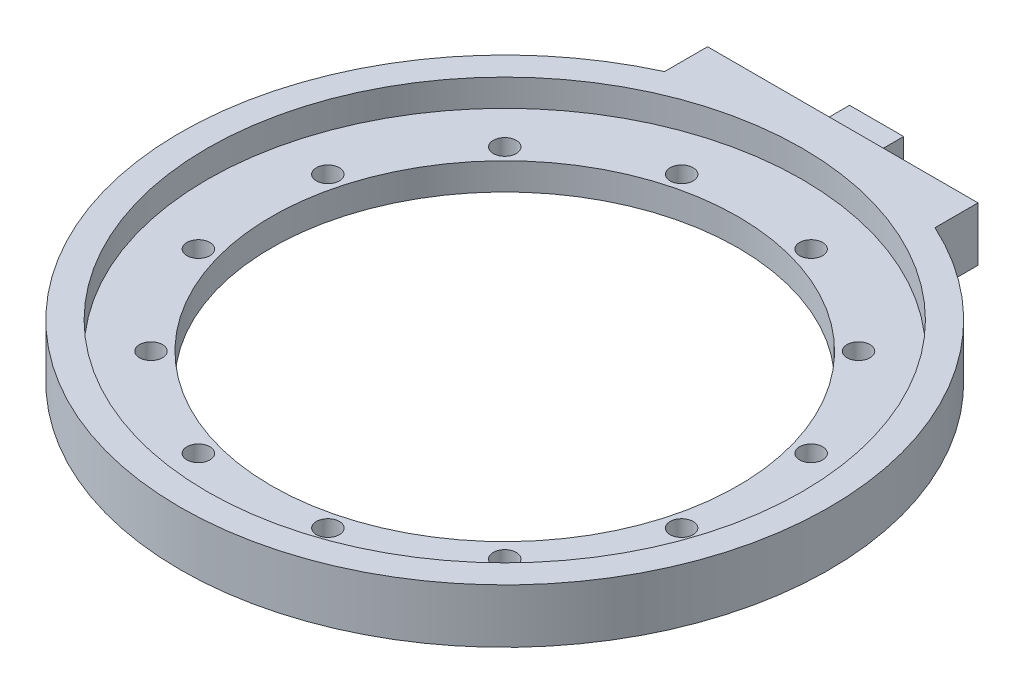
SolidWorks part; units mm, degrees
ref_plane "前视基准面" through (0, 0, 0) normal (0, 0, 1) x (1, 0, 0)
ref_plane "上视基准面" through (0, 0, 0) normal (0, 1, 0) x (1, 0, 0)
ref_plane "右视基准面" through (0, 0, 0) normal (1, 0, 0) x (0, 0, -1)
sketch "草图1" plane through (0, 0, 0) normal (0, 0, 1) x (1, 0, 0)
  circle A3 centre (0, 0) radius 26.5
extrude "凸台-拉伸1" add sketch "草图1" along normal blind 5
hole_wizard "M4 六角凹头盖的柱孔1" positions "3D草图2" profile "草图3" counterbore size "M4" standard "BSI"
sketch3d "3D草图2"
  point P14 (-13.9806, 16.6615, 0)
  point P34 (-13.9806, 16.6615, 5)
  point P36 (13.9806, 16.6615, 5)
  point P38 (-21.75, 0, 5)
  point P40 (-13.9806, -16.6615, 5)
  point P42 (13.9806, -16.6615, 5)
  point P44 (21.75, 0, 5)
sketch "草图3" plane through (21.75, 0, 5) normal (1, 0, 0) x (0, -1, 0)
  line L0 (0, 0) -> (0, 5)
  line L1 (0, 5) -> (2.25, 5)
  line L3 (2.25, 5) -> (2.25, 4)
  line L4 (2.25, 4) -> (4, 4)
  line L5 (4, 4) -> (4, 0)
  line L7 (4, 0) -> (0, 0)
  line L11 (0, -6.35) -> (0, 107.95) construction
  dimension "通孔孔直径" = 4.5
  dimension "通孔孔深度" = 5
  dimension "柱形沉头孔直径" = 8
  dimension "柱形沉头孔深度" = 4
ref_plane "基准面1" through (0, 0, 5) normal (0, 0, 1) x (1, 0, 0)
sketch "参考" plane through (0, 0, 5) normal (0, 0, 1) x (1, 0, 0)
  line L12 (-20.7304, 8.7) -> (19.3146, 8.7) construction
ref_plane "基准面3" through (0, 8.7, 0) normal (0, -1, 0) x (1, 0, 0)
sketch "草图5" plane through (0, 8.7, 0) normal (0, -1, 0) x (1, 0, 0)
  line L1 (-20.7304, 5) -> (19.3146, 5) construction
  line L4 (-20, 5) -> (-20, 11.3652)
  line L5 (-20, 5) -> (20, 5)
  line L7 (20, 5) -> (20, 11.3652)
  arc A6 (-20, 11.3652) -> (20, 11.3652) centre (0, 55) cw
extrude "盘面" add sketch "草图5" against normal blind 8
sketch "草图8" plane through (0, 8.7, 0) normal (0, -1, 0) x (1, 0, 0)
  circle A1 centre (0, 55) radius 34.5
extrude "盘面切割" cut sketch "草图8" against normal through all
hole_wizard "M3 六角凹头盖的柱孔1" positions "3D草图3" profile "草图10" counterbore size "M3" standard "BSI" end condition through all
sketch3d "3D草图3"
  line L0 (0, 16.7, 55) -> (0, 8.7, 55) construction
  line L5 (0, 16.7, 55) -> (9.5763, 16.7, 19.2607)
  line L7 (0, 16.7, 55) -> (-9.5763, 16.7, 90.7393)
  line L11 (26.163, 16.7, 28.837) -> (0, 16.7, 55)
  line L17 (35.7393, 16.7, 45.4237) -> (0, 16.7, 55)
  line L19 (0, 16.7, 55) -> (35.7393, 16.7, 64.5763)
  line L21 (0, 16.7, 55) -> (26.6194, 16.7, 81.6194)
  line L22 (0, 16.7, 55) -> (-26.163, 16.7, 28.837)
  line L37 (0, 16.7, 55) -> (9.5763, 16.7, 90.7393)
  line L44 (-9.5763, 16.7, 19.2607) -> (0, 16.7, 55)
  line L54 (0, 16.7, 55) -> (-35.7393, 16.7, 45.4237)
  line L56 (0, 16.7, 55) -> (-26.163, 16.7, 81.163)
  line L68 (0, 16.7, 55) -> (-35.7393, 16.7, 64.5763)
  point P19 (9.5763, 16.7, 19.2607)
  point P34 (26.163, 16.7, 28.837)
  point P43 (35.7393, 16.7, 45.4237)
  point P46 (35.7393, 16.7, 64.5763)
  point P49 (26.6194, 16.7, 81.6194)
  point P169 (9.5763, 16.7, 90.7393)
  point P171 (-9.5763, 16.7, 90.7393)
  point P173 (-26.163, 16.7, 81.163)
  point P181 (-26.163, 16.7, 28.837)
  point P183 (-35.7393, 16.7, 45.4237)
  point P185 (-35.7393, 16.7, 64.5763)
  point P187 (-9.5763, 16.7, 19.2607)
sketch "草图10" plane through (-9.5763, 16.7, 19.2607) normal (1, 0, 0) x (0, 0, 1)
  line L0 (0, 0) -> (0, 43.2)
  line L1 (0, 43.2) -> (1.7, 43.2)
  line L3 (1.7, 43.2) -> (1.7, 3)
  line L4 (1.7, 3) -> (3.25, 3)
  line L5 (3.25, 3) -> (3.25, 0)
  line L7 (3.25, 0) -> (0, 0)
  line L11 (0, -6.35) -> (0, 107.95) construction
  dimension "通孔孔直径" = 3.4
  dimension "通孔孔深度" = 43.2
  dimension "柱形沉头孔直径" = 6.5
  dimension "柱形沉头孔深度" = 3
sketch "草图11" plane through (0, 0, 0) normal (0, 0, 1) x (1, 0, 0)
  line L17 (-20.7304, 8.7) -> (19.3146, 8.7) construction
  line L19 (-4, 14.7) -> (4, 14.7)
  line L20 (4, 14.7) -> (4, 11.7)
  line L21 (4, 11.7) -> (12, 11.7)
  line L22 (12, 11.7) -> (12, 8.7)
  line L23 (12, 8.7) -> (-12, 8.7)
  line L24 (-12, 11.7) -> (-12, 8.7)
  line L25 (-4, 11.7) -> (-12, 11.7)
  line L26 (-4, 14.7) -> (-4, 11.7)
  circle A1 centre (0, 0) radius 26.5
extrude "切除-拉伸1" cut sketch "草图11" along normal blind 5
ref_plane "基准面4" through (0, 16.7, 0) normal (0, 1, 0) x (1, 0, 0)
sketch "草图12" plane through (0, 16.7, 0) normal (0, 1, 0) x (1, 0, 0)
  circle A0 centre (0, -55) radius 44
extrude "切除-拉伸6" cut sketch "草图12" against normal blind 4
